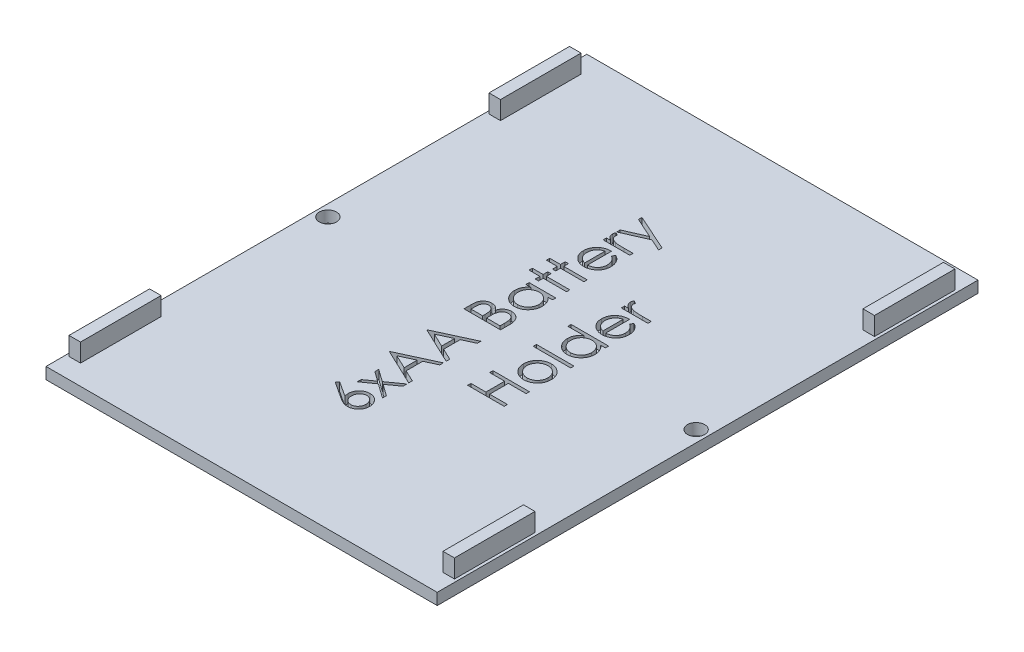
SolidWorks part; units mm, degrees
ref_plane "Front Plane" through (0, 0, 0) normal (0, 0, 1) x (1, 0, 0)
ref_plane "Top Plane" through (0, 0, 0) normal (0, 1, 0) x (1, 0, 0)
ref_plane "Right Plane" through (0, 0, 0) normal (1, 0, 0) x (0, 0, -1)
sketch "Sketch1" plane through (0, 0, 0) normal (0, 1, 0) x (1, 0, 0)
  line L1 (-34, -47) -> (34, -47)
  line L2 (-34, -47) -> (-34, 47)
  line L3 (-34, 47) -> (34, 47)
  line L4 (34, -47) -> (34, 47)
  line L5 (-34, -47) -> (34, 47) construction
  line L6 (-34, 47) -> (34, -47) construction
  point P0 (0, 0)
  dimension "D1" = 68
  dimension "D2" = 94
extrude "Boss-Extrude1" add sketch "Sketch1" along normal blind 2
sketch "Sketch2" plane through (0, 2, 0) normal (0, 1, 0) x (1, 0, 0)
  line L1 (-33.5, -43.5) -> (-31.5, -43.5)
  line L2 (-33.5, -43.5) -> (-33.5, -29.5)
  line L3 (-33.5, -29.5) -> (-31.5, -29.5)
  line L4 (-31.5, -43.5) -> (-31.5, -29.5)
  line L5 (-34, -47) -> (34, -47) construction
  line L6 (-34, 47) -> (-34, -47) construction
  dimension "D1" = 14
  dimension "D2" = 3.5
  dimension "D3" = 2
  dimension "D4" = 0.5
extrude "Boss-Extrude2" add sketch "Sketch2" along normal blind 3.175 contours L3 L4 L1 L2
mirror "Mirror1" about plane through (0, 0, 0) normal (1, 0, 0) of "Boss-Extrude2"
mirror "Mirror2" about plane through (0, 0, 0) normal (0, 0, 1) of "Mirror1", "Boss-Extrude2"
sketch "Sketch3" plane through (0, 2, 0) normal (0, 1, 0) x (1, 0, 0)
  line L0 (0, -31.5804) -> (0, 31.5804) construction
  line L1 (-34, -47) -> (34, -47) construction
  text T0 "6xAA Battery\r\nHolder" font "Century Gothic" height in points 24
  point P5 (0, -47)
  point P6 (0, 0)
  point P7 (0, 0)
  point P8 (0, 15.5843)
  point P9 (0, 0)
  point P10 (0, 0)
  point P11 (0, 0)
  point P12 (0, 0)
  point P14 (0, 23.9448)
  point P15 (0, 0)
  dimension "D1" = 63.1609
extrude "Cut-Extrude1" cut sketch "Sketch3" against normal blind 1.5
sketch "Sketch4" plane through (0, 2, 0) normal (0, 1, 0) x (1, 0, 0)
  line L0 (-34, 47) -> (-34, -47) construction
  circle A0 centre (-32, 0) radius 1.5
  dimension "D2" = 3
  dimension "D1" = 2
extrude "Cut-Extrude2" cut sketch "Sketch4" against normal through all
mirror "Mirror3" about plane through (0, 0, 0) normal (1, 0, 0) of "Cut-Extrude2"
